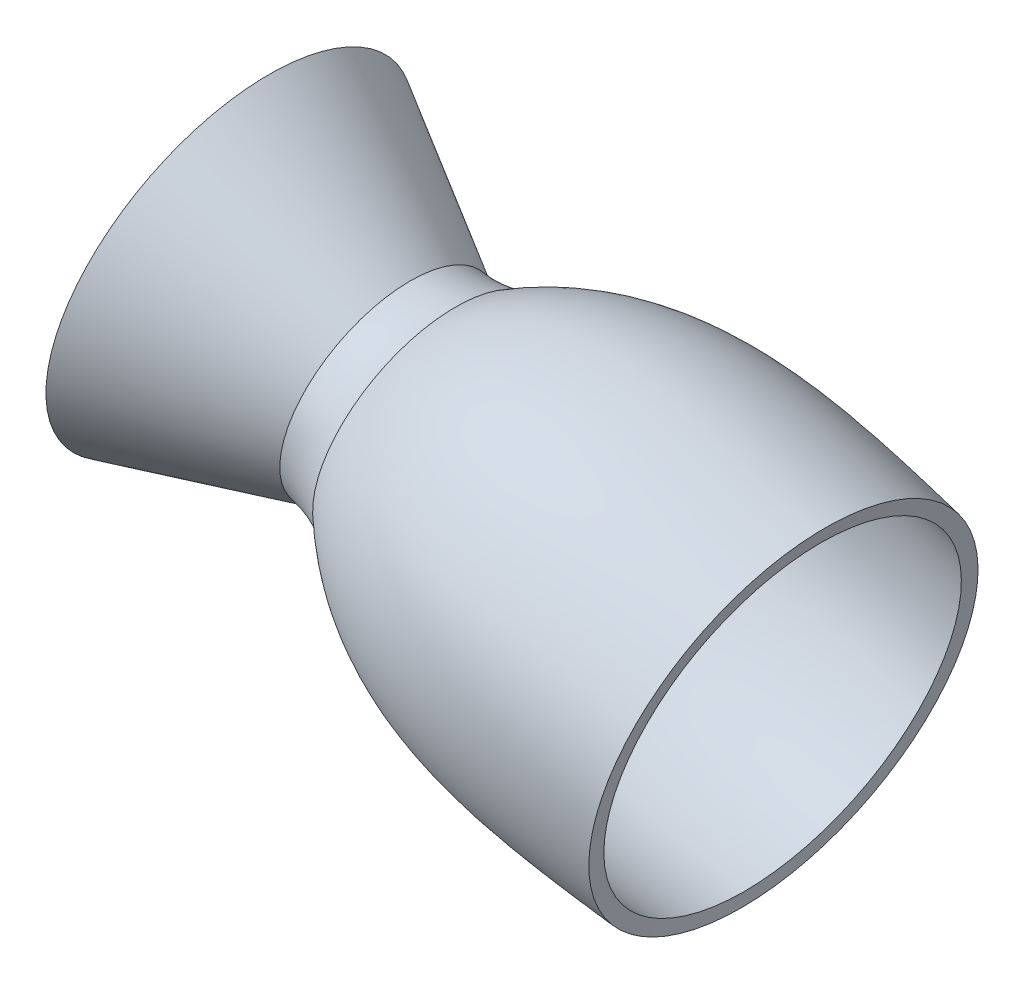
SolidWorks part; units mm, degrees
ref_plane "Front Plane" through (0, 0, 0) normal (0, 0, 1) x (1, 0, 0)
ref_plane "Top Plane" through (0, 0, 0) normal (0, 1, 0) x (1, 0, 0)
ref_plane "Right Plane" through (0, 0, 0) normal (1, 0, 0) x (0, 0, -1)
sketch "Sketch2" plane through (0, 0, 0) normal (0, 0, 1) x (1, 0, 0)
  line L0 (-43.7162, 70.9462) -> (-180.2199, 175.3704)
  line L1 (-43.7162, 58.8714) -> (-180.2199, 162.633)
  line L2 (-180.2199, 162.633) -> (-180.2199, 175.3704)
  line L3 (353.0873, 50.399) -> (357.1662, 64.8338)
  line L4 (-43.7162, -32.9541) -> (181.4333, -83.7495) construction
  arc A0 (7.1949, 57.7844) -> (-43.7162, 58.8714) centre (-17.4734, 95.1979) cw
  arc A1 (0, 70.9462) -> (-43.7162, 70.9462) centre (-21.8581, 175.3704) cw
  spline S0 degree 3 poles (0, 70.9462) (117.6311, 135.2487) (241.6014, 97.4896) (357.1662, 64.8338) knots 0 0 0 0 1 1 1 1
  spline S1 degree 1 poles (7.1949, 57.7844) (353.0873, 50.399) knots 0 0 1 1 construction
  spline S2 degree 3 poles (7.1949, 57.7844) (8.9289, 58.7323) (12.4306, 60.5976) (19.4074, 64.1218) (28.1532, 68.1874) (38.6661, 72.5315) (52.7178, 77.6432) (70.3482, 82.8056) (91.6249, 87.192) (113.0299, 89.9154) (141.7415, 91.5158) (177.9376, 90.0509) (221.7226, 83.8555) (265.6594, 74.3708) (302.2162, 64.7221) (331.3526, 56.562) (345.8346, 52.4484) (353.0873, 50.399) knots 0 0 0 0 0.015625 0.03125 0.0625 0.09375 0.125 0.1875 0.25 0.3125 0.375 0.5 0.625 0.75 0.875 0.9375 1 1 1 1
  dimension "D1" = 15
revolve "Revolve2" add sketch "Sketch2" angle 360 about L4
